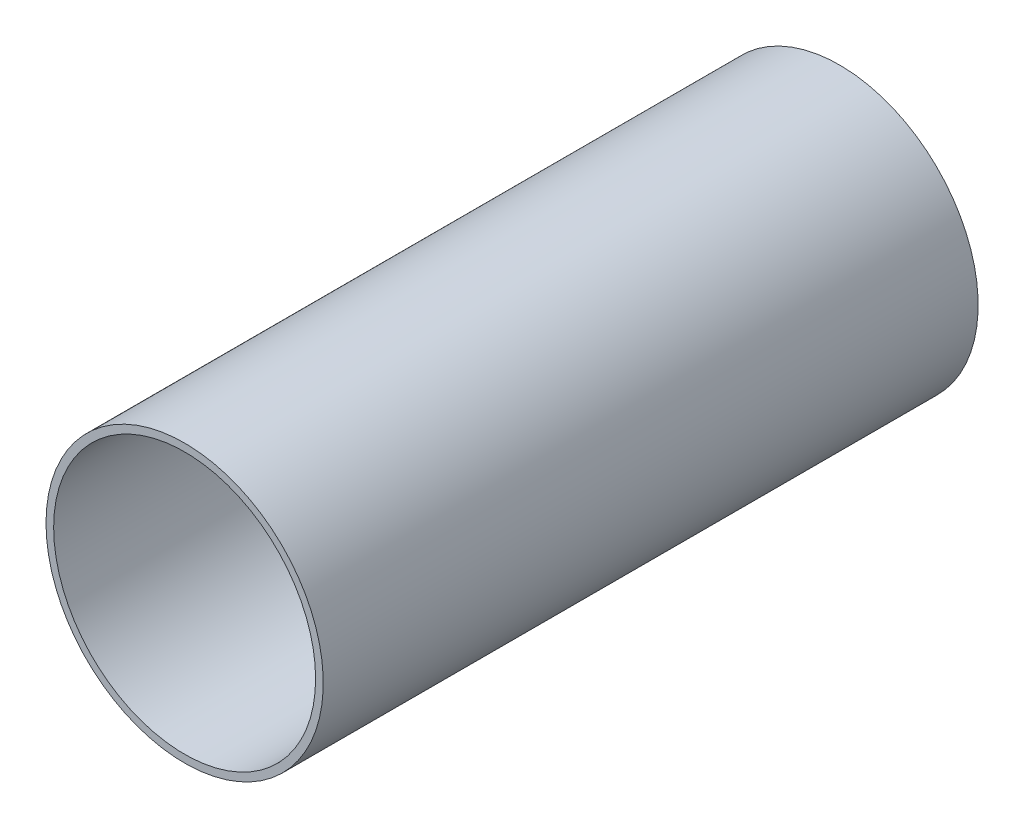
SolidWorks part; units mm, degrees
ref_plane "前基準面" through (0, 0, 0) normal (0, 0, 1) x (1, 0, 0)
ref_plane "上基準面" through (0, 0, 0) normal (0, 1, 0) x (1, 0, 0)
ref_plane "右基準面" through (0, 0, 0) normal (1, 0, 0) x (0, 0, -1)
sketch "草圖1" plane through (0, 0, 0) normal (0, 0, 1) x (1, 0, 0)
  circle A0 centre (0, 0) radius 19.05
  circle A1 centre (0, 0) radius 18
  dimension "D1" = 36
  dimension "D2" = 38.1
extrude "填料-伸長1" add sketch "草圖1" along normal blind 90
